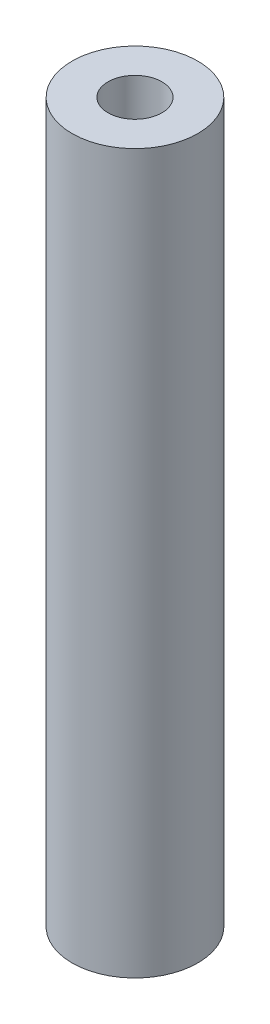
SolidWorks part; units mm, degrees
ref_plane "Alzado" through (0, 0, 0) normal (0, 0, 1) x (1, 0, 0)
ref_plane "Planta" through (0, 0, 0) normal (0, 1, 0) x (1, 0, 0)
ref_plane "Vista lateral" through (0, 0, 0) normal (1, 0, 0) x (0, 0, -1)
sketch "Croquis1" plane through (0, 0, 0) normal (0, 1, 0) x (1, 0, 0)
  circle A0 centre (0, 0) radius 1.5
  circle A1 centre (0, 0) radius 3.5
  dimension "D1" = 3
  dimension "D2" = 7
extrude "Saliente-Extruir1" add sketch "Croquis1" along normal blind 40
